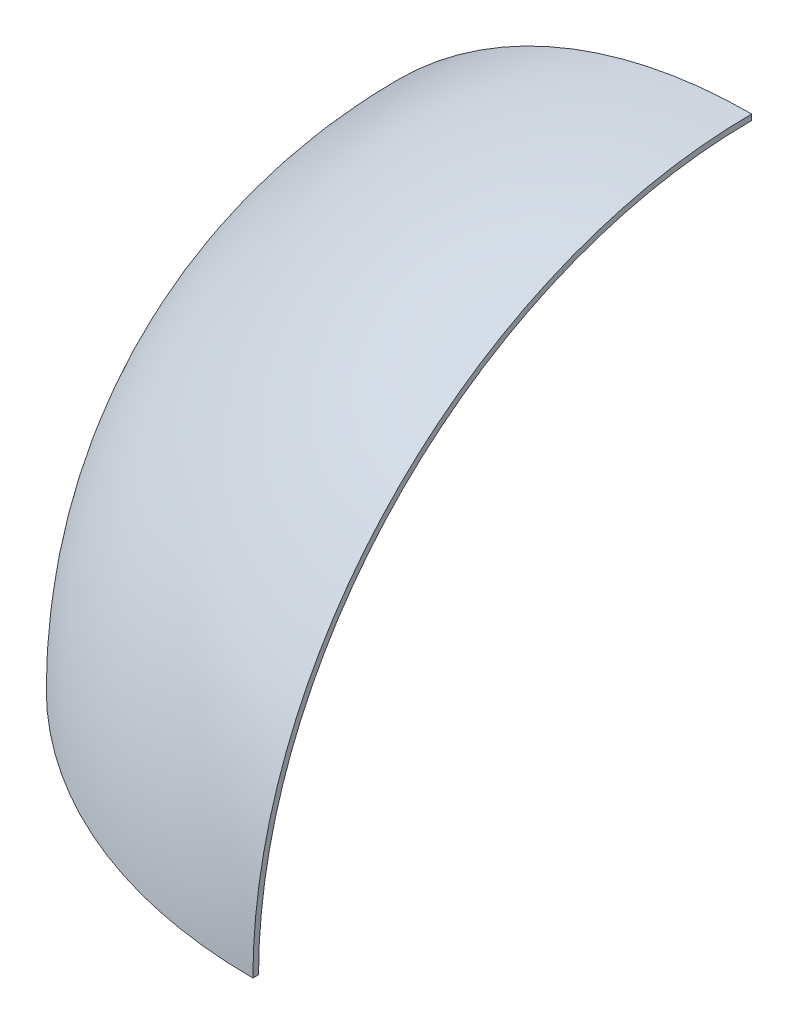
SolidWorks part; units mm, degrees
ref_plane "Front Plane" through (0, 0, 0) normal (0, 0, 1) x (1, 0, 0)
ref_plane "Top Plane" through (0, 0, 0) normal (0, 1, 0) x (1, 0, 0)
ref_plane "Right Plane" through (0, 0, 0) normal (1, 0, 0) x (0, 0, -1)
sketch "Sketch1" plane through (0, 0, 0) normal (0, 0, 1) x (1, 0, 0)
  line L0 (-88, 0) -> (-87, 0) construction
  line L1 (-87, 0) -> (0, 0) construction
  line L2 (0, 87) -> (0, 88)
  line L3 (0, 0) -> (0, 87) construction
  line L4 (0, 87) -> (0, 88) construction
  line L5 (-88, 0) -> (-87, 0)
  arc A0 (0, 88) -> (-88, 0) centre (0, 0) ccw
  arc A1 (0, 87) -> (-87, 0) centre (0, 0) ccw
revolve "Revolve1" add sketch "Sketch1" angle 90 about L3
